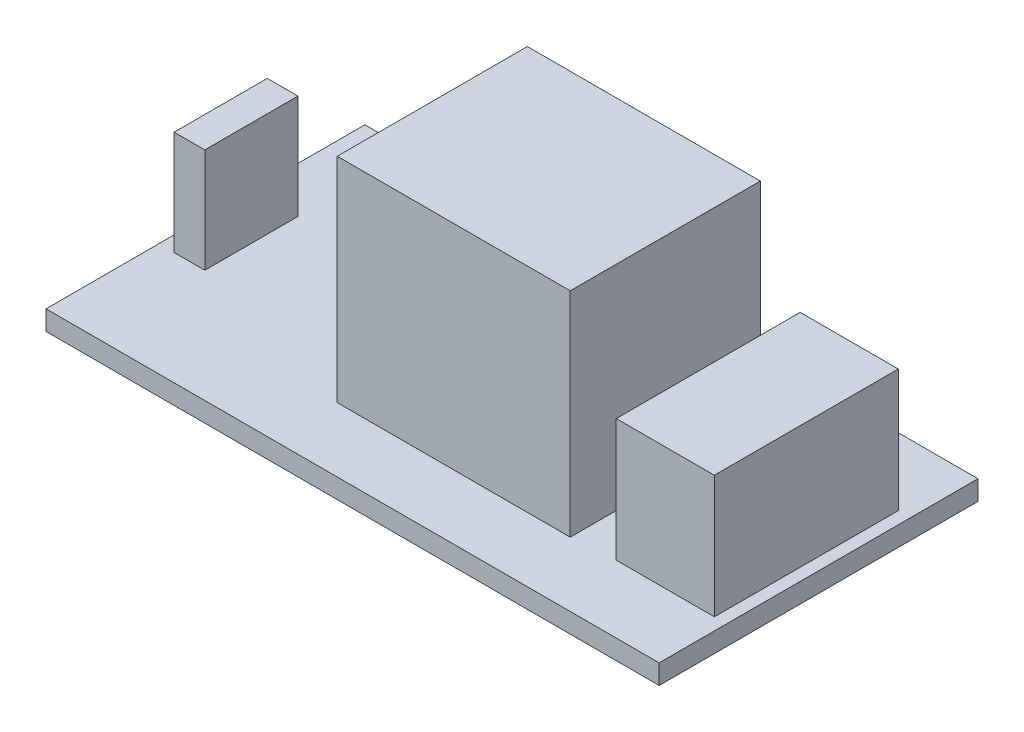
SolidWorks part; units mm, degrees
ref_plane "Front Plane" through (0, 0, 0) normal (0, 0, 1) x (1, 0, 0)
ref_plane "Top Plane" through (0, 0, 0) normal (0, 1, 0) x (1, 0, 0)
ref_plane "Right Plane" through (0, 0, 0) normal (1, 0, 0) x (0, 0, -1)
other "Configuration Table"
sketch "Sketch1" plane through (0, 0, 0) normal (0, 1, 0) x (1, 0, 0)
  line L1 (-25, -13) -> (25, -13)
  line L2 (-25, -13) -> (-25, 13)
  line L3 (-25, 13) -> (25, 13)
  line L4 (25, -13) -> (25, 13)
  line L5 (-25, -13) -> (25, 13) construction
  line L6 (-25, 13) -> (25, -13) construction
  point P6 (0, 0)
  dimension "D1" = 50
  dimension "D2" = 26
extrude "Board" add sketch "Sketch1" along normal blind 1.6
sketch "Sketch2" plane through (0, 0, 0) normal (0, 1, 0) x (1, 0, 0)
  line L0 (-6.5, -7.75) -> (12.5, -7.75)
  line L1 (12.5, -7.75) -> (12.5, 7.75)
  line L2 (12.5, 7.75) -> (-6.5, 7.75)
  line L3 (-6.5, 7.75) -> (-6.5, -7.75)
extrude "Relay" add sketch "Sketch2" along normal blind 17.4 from offset 1.6
sketch "Sketch3" plane through (0, 0, 0) normal (0, 1, 0) x (1, 0, 0)
  line L0 (16, -7.5) -> (24, -7.5)
  line L1 (24, -7.5) -> (24, 7.5)
  line L2 (24, 7.5) -> (16, 7.5)
  line L3 (16, 7.5) -> (16, -7.5)
extrude "Terminal_Block" add sketch "Sketch3" along normal blind 10 from offset 1.6
sketch "Sketch4" plane through (0, 0, 0) normal (0, 1, 0) x (1, 0, 0)
  line L0 (-23.75, -3.8) -> (-21.25, -3.8)
  line L1 (-21.25, -3.8) -> (-21.25, 3.8)
  line L2 (-21.25, 3.8) -> (-23.75, 3.8)
  line L3 (-23.75, 3.8) -> (-23.75, -3.8)
extrude "Header" add sketch "Sketch4" along normal blind 8.5 from offset 1.6
equation "\"Jar_OD\"= 90  'ASSUMED - Part G fallback - jar outer diameter"
equation "\"Jar_H\"= 120  'ASSUMED - Part G fallback - jar height"
equation "\"Pump_L\"= 45  'ASSUMED - Part G fallback"
equation "\"Pump_W\"= 24  'ASSUMED - Part G fallback"
equation "\"Pump_H\"= 33  'ASSUMED - Part G fallback"
equation "\"Pump_Outlet_OD\"= 7.5  'ASSUMED - Part G fallback"
equation "\"Tube_OD\"= 8  'ASSUMED - Part G fallback"
equation "\"Tube_ID\"= 6  'ASSUMED - Part G fallback"
equation "\"TDS_Body_Dia\"= 12  'ASSUMED - Part G fallback"
equation "\"TDS_Wet_Len\"= 45  'ASSUMED - Part G fallback - length in water"
equation "\"DS_Tube_Dia\"= 6  'ASSUMED - Part G fallback"
equation "\"DS_Tube_Len\"= 50  'ASSUMED - Part G fallback"
equation "\"ORP_Body_Dia\"= 12  'ASSUMED - Part G fallback"
equation "\"ORP_Body_Len\"= 150  'ASSUMED - Part G fallback"
equation "\"ORP_Cap_Dia\"= 16  'ASSUMED - Part G fallback"
equation "\"Turb_W\"= 33  'ASSUMED - Part G fallback - head width"
equation "\"Turb_D\"= 28  'ASSUMED - Part G fallback - head depth"
equation "\"Turb_H\"= 30  'ASSUMED - Part G fallback - head height"
equation "\"Turb_Slot_W\"= 10  'ASSUMED - Part G fallback - slot width"
equation "\"Flow_L\"= 62  'ASSUMED - Part G fallback YF-S201"
equation "\"Flow_W\"= 36  'ASSUMED - Part G fallback"
equation "\"Flow_H\"= 35  'ASSUMED - Part G fallback"
equation "\"Thread_G12_OD\"= 20.955  'ASSUMED - Part G fallback thread G1/2 (major diameter)"
equation "\"Valve_L\"= 75  'ASSUMED - Part G fallback"
equation "\"Valve_W\"= 45  'ASSUMED - Part G fallback"
equation "\"Valve_H\"= 60  'ASSUMED - Part G fallback"
equation "\"Tee_L\"= 40  'ASSUMED - Part G fallback - overall length"
equation "\"Tee_Branch_L\"= 25  'ASSUMED - Part G fallback"
equation "\"Tee_OD\"= 12  'ASSUMED - Part G fallback"
equation "\"Cuv_W\"= 12.5  'ASSUMED - old R3 cuvette (station suppressed in SS4)"
equation "\"Cuv_D\"= 12.5  'ASSUMED - old R3 cuvette (station suppressed in SS4)"
equation "\"Cuv_H\"= 45  'ASSUMED - old R3 cuvette (station suppressed in SS4)"
equation "\"LED_Board_L\"= 20  'ASSUMED - Part G fallback"
equation "\"LED_Board_W\"= 20  'ASSUMED - Part G fallback - LED at centre"
equation "\"GUVA_L\"= 20  'ASSUMED - Part G fallback"
equation "\"GUVA_W\"= 12  'ASSUMED - Part G fallback - sensor at centre"
equation "\"Reed_L\"= 27  'ASSUMED - Part G fallback MC-38 half"
equation "\"Reed_W\"= 14  'ASSUMED - Part G fallback"
equation "\"Reed_H\"= 8  'ASSUMED - Part G fallback"
equation "\"ESP_L\"= 51  'ASSUMED - Part G fallback"
equation "\"ESP_W\"= 28  'ASSUMED - Part G fallback"
equation "\"TFT_L\"= 58  'ASSUMED - Part G fallback - board"
equation "\"TFT_W\"= 35  'ASSUMED - Part G fallback - board"
equation "\"TFT_Win_L\"= 35  'ASSUMED - Part G fallback - visible window"
equation "\"TFT_Win_W\"= 28  'ASSUMED - Part G fallback - visible window"
equation "\"Relay_L\"= 50  'ASSUMED - Part G fallback"
equation "\"Relay_W\"= 26  'ASSUMED - Part G fallback"
equation "\"Relay_H\"= 19  'ASSUMED - Part G fallback"
equation "\"Mosfet_L\"= 34  'ASSUMED - Part G fallback"
equation "\"Mosfet_W\"= 17  'ASSUMED - Part G fallback"
equation "\"Mosfet_H\"= 12  'ASSUMED - Part G fallback"
equation "\"TDS_Board_L\"= 42  'ASSUMED - Part G fallback"
equation "\"TDS_Board_W\"= 32  'ASSUMED - Part G fallback"
equation "\"Turb_Board_L\"= 38  'ASSUMED - Part G fallback"
equation "\"Turb_Board_W\"= 28  'ASSUMED - Part G fallback"
equation "\"BNC_Thread_Dia\"= 9.5  'ASSUMED - Part G fallback"
equation "\"Plate_L\"= 420  'ASSUMED - Part G fallback"
equation "\"Plate_W\"= 297  'ASSUMED - Part G fallback"
equation "\"Plate_T\"= 6  'ASSUMED - Part G fallback"
equation "\"Probe_Clr\"= 0.3  'DESIGN VALUE - Part C rule 3 - printed probe hole = diameter + 0.3"
equation "\"Cuv_Clr\"= 0.2  'DESIGN VALUE - Part C rule 3 - cuvette pocket = size + 0.2"
equation "\"Label_H\"= 0.6  'DESIGN VALUE - Part D - raised label height"
equation "\"D1@Sketch1\" = \"Relay_L\""
equation "\"D2@Sketch1\" = \"Relay_W\""
equation "\"Booster_L\"= 150  'ASSUMED - Part G fallback - booster pump"
equation "\"Booster_W\"= 95  'ASSUMED - Part G fallback"
equation "\"Booster_H\"= 100  'ASSUMED - Part G fallback"
equation "\"PTube_OD\"= 6.35  'ASSUMED - Part G fallback - product tube 1/4 inch"
equation "\"Qz_Out\"= 12  'ASSUMED - Part G fallback - quartz channel outside square"
equation "\"Qz_Path\"= 10  'ASSUMED - Part G fallback - quartz channel inside light path"
equation "\"Qz_L\"= 40  'ASSUMED - Part G fallback - quartz channel length"
equation "\"LED860_Dia\"= 5  'ASSUMED - Part G fallback - 860 nm LED"
equation "\"BPW_L\"= 5.4  'ASSUMED - Part G fallback - BPW34"
equation "\"BPW_W\"= 4.3  'ASSUMED - Part G fallback - BPW34"
equation "\"Cart_Dia\"= 50  'ASSUMED - Part G fallback - sediment and pre-carbon cartridges"
equation "\"Cart_L\"= 255  'ASSUMED - Part G fallback"
equation "\"UF_Dia\"= 50  'ASSUMED - Part G fallback - UF cartridge"
equation "\"UF_L\"= 260  'ASSUMED - Part G fallback"
equation "\"RO_Dia\"= 62  'ASSUMED - Part G fallback - RO membrane housing"
equation "\"RO_L\"= 300  'ASSUMED - Part G fallback"
equation "\"UVC_Dia\"= 40  'ASSUMED - Part G fallback - UV-C chamber"
equation "\"UVC_L\"= 300  'ASSUMED - Part G fallback"
equation "\"Tank_W\"= 260  'ASSUMED - Part G fallback - storage tank"
equation "\"Tank_D\"= 160  'ASSUMED - Part G fallback"
equation "\"Tank_H\"= 300  'ASSUMED - Part G fallback"
equation "\"Cab_W\"= 400  'ASSUMED - Part G fallback - purifier cabinet"
equation "\"Cab_D\"= 270  'ASSUMED - Part G fallback"
equation "\"Cab_H\"= 560  'ASSUMED - Part G fallback"
equation "\"ORP_Board_L\"= 40  'ASSUMED - Part G fallback - ORP buffer board"
equation "\"ORP_Board_W\"= 30  'ASSUMED - Part G fallback"
equation "\"Opt_Board_L\"= 50  'ASSUMED - Part G fallback - optical front-end board"
equation "\"Opt_Board_W\"= 40  'ASSUMED - Part G fallback"
equation "\"Buck_L\"= 43  'ASSUMED - Part G fallback - 12 V to 5 V buck module"
equation "\"Buck_W\"= 21  'ASSUMED - Part G fallback"
equation "\"Buck_H\"= 14  'ASSUMED - Part G fallback"
equation "\"BB_L\"= 165  'ASSUMED - Part G fallback - breadboard (As_Built_R3 only)"
equation "\"BB_W\"= 55  'ASSUMED - Part G fallback"
equation "\"BB_H\"= 10  'ASSUMED - Part G fallback"
